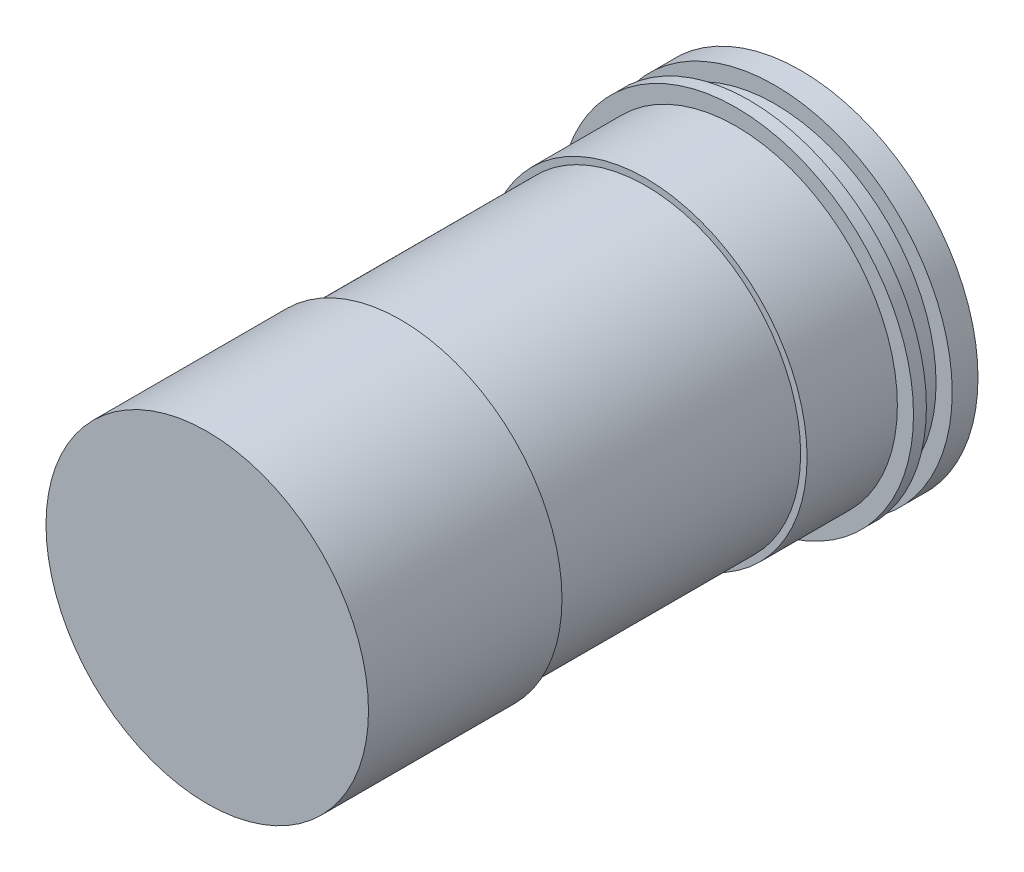
SolidWorks part; units mm, degrees
ref_plane "Front Plane" through (0, 0, 0) normal (0, 0, 1) x (1, 0, 0)
ref_plane "Top Plane" through (0, 0, 0) normal (0, 1, 0) x (1, 0, 0)
ref_plane "Right Plane" through (0, 0, 0) normal (1, 0, 0) x (0, 0, -1)
sketch "Sketch1" plane through (0, 0, 0) normal (0, 0, 1) x (1, 0, 0)
  line L1 (-17, 14.5) -> (17, 14.5) construction
  line L2 (-17, 14.5) -> (-17, -14.5) construction
  line L3 (-17, -14.5) -> (17, -14.5) construction
  line L4 (17, 14.5) -> (17, -14.5) construction
  line L5 (-17, 14.5) -> (17, -14.5) construction
  line L6 (-17, -14.5) -> (17, 14.5) construction
  circle A0 centre (0, 0) radius 12.5
  point P0 (0, 0)
  dimension "D3" = 25
  dimension "D1" = 34
  dimension "D2" = 29
extrude "Boss-Extrude1" add sketch "Sketch1" along normal mid plane 7 contours L2 L3 L4 L1 | A0
sketch "Sketch4" plane through (0, 0, 0) normal (0, 1, 0) x (1, 0, 0)
  line L0 (-12.5, 3.5) -> (0, 3.5)
  line L1 (-12.5, 3.5) -> (-12.5, 11.5)
  line L2 (-12.5, 11.5) -> (-12, 11.5)
  line L3 (-12, 11.5) -> (-12, 30.5)
  line L4 (-12, 30.5) -> (-12.5, 30.5)
  line L5 (-12.5, 30.5) -> (-12.5, 37.5)
  line L6 (-12.5, 37.5) -> (-13.75, 37.5)
  line L7 (-13.75, 37.5) -> (-13.75, 38.5)
  line L8 (-13.75, 38.5) -> (-12.5, 38.5)
  line L9 (-12.5, 38.5) -> (-12.5, 40.5)
  line L10 (-12.5, 40.5) -> (-13.75, 40.5)
  line L11 (-13.75, 40.5) -> (-13.75, 42.5)
  line L12 (-13.75, 42.5) -> (0, 42.5)
  line L13 (-12.5, 3.5) -> (11.57, 3.5) construction
  line L15 (0, 42.5) -> (0, 3.5) construction
  line L16 (0, 3.5) -> (0, 42.5)
  line L19 (-12.5, -3.5) -> (12.5, -3.5) construction
  point P12 (0, 0)
  point P17 (-4.5, 3.5)
  point P18 (0, 0)
  point P20 (0, 0)
  point P23 (0, 0)
  point P25 (-11.57, 3.5978)
  dimension "D1" = 8
  dimension "D2" = 46
  dimension "D3" = 2
  dimension "D4" = 1
  dimension "D5" = 2
  dimension "D6" = 7
  dimension "D7" = 13.75
  dimension "D8" = 0.5
revolve "Revolve1" add sketch "Sketch4" angle 360 about L16
sketch "Sketch5" plane through (0, 0, -42.5) normal (0, 0, -1) x (-1, 0, 0)
  circle A0 centre (0, 0) radius 9.75
  circle A2 centre (0, 0) radius 13.75 construction
  dimension "D1" = 4
extrude "Cut-Extrude2" cut sketch "Sketch5" against normal blind 5 draft 45
sketch "Sketch6" plane through (0, 0, 0) normal (0, 1, 0) x (1, 0, 0)
  line L0 (-4.75, 37.5) -> (0, 37.5)
  line L1 (0, 37.5) -> (0, 42.25)
  line L2 (4.75, 37.5) -> (-4.75, 37.5) construction
  line L3 (-9.75, 42.5) -> (-4.75, 37.5) construction
  line L4 (-4.75, 37.5) -> (4.75, 37.5) construction
  line L5 (4.75, 37.5) -> (9.75, 42.5) construction
  arc A0 (-4.75, 37.5) -> (0, 42.25) centre (0, 37.5) cw
revolve "Revolve2" add sketch "Sketch6" angle 360 about L1
